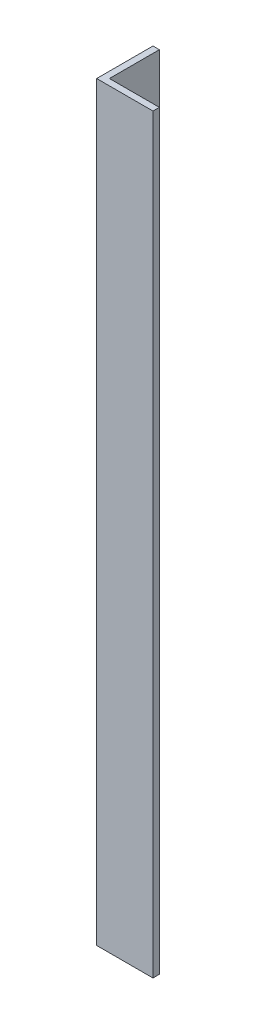
SolidWorks part; units mm, degrees
ref_plane "Front Plane" through (0, 0, 0) normal (0, 0, 1) x (1, 0, 0)
ref_plane "Top Plane" through (0, 0, 0) normal (0, 1, 0) x (1, 0, 0)
ref_plane "Right Plane" through (0, 0, 0) normal (1, 0, 0) x (0, 0, -1)
sketch "Sketch1" plane through (0, 0, 0) normal (0, 1, 0) x (1, 0, 0)
  line L0 (0, 0) -> (0, 30)
  line L1 (0, 0) -> (30, 0)
  line L2 (0, 30) -> (3.4, 30)
  line L3 (30, 0) -> (30, 3.4)
  line L6 (3.4, 30) -> (3.4, 3.4)
  line L7 (3.4, 3.4) -> (30, 3.4)
extrude "Boss-Extrude1" add sketch "Sketch1" along normal blind 400
